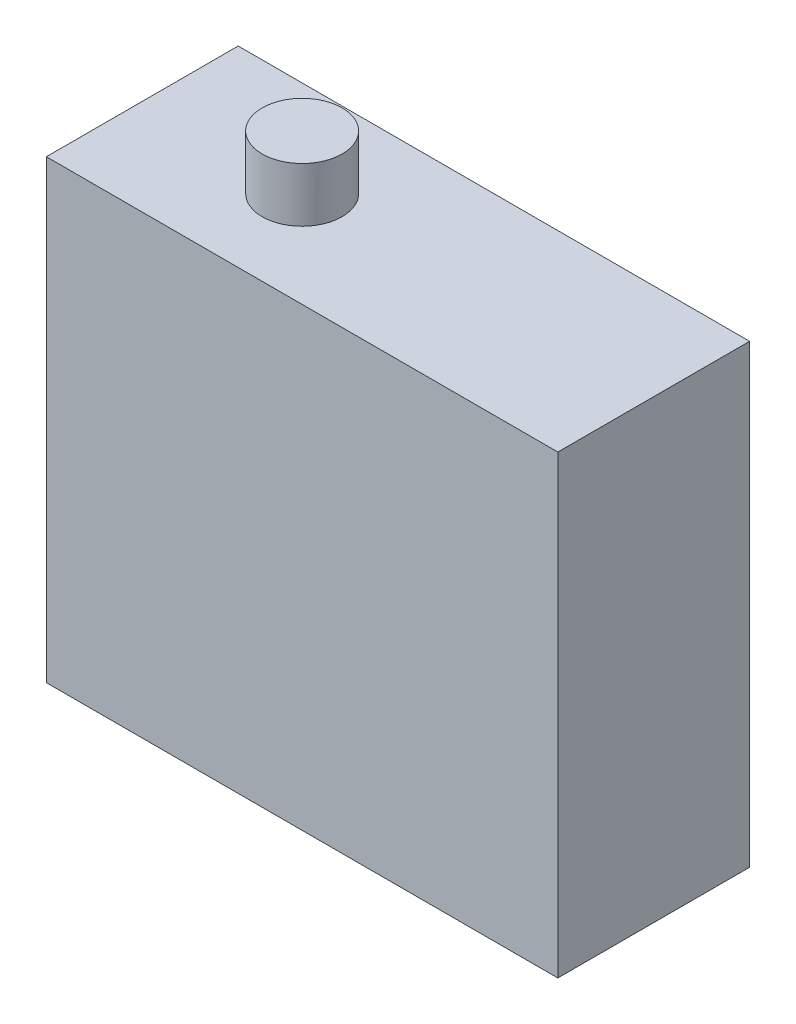
SolidWorks part; units mm, degrees
ref_plane "前视基准面" through (0, 0, 0) normal (0, 0, 1) x (1, 0, 0)
ref_plane "上视基准面" through (0, 0, 0) normal (0, 1, 0) x (1, 0, 0)
ref_plane "右视基准面" through (0, 0, 0) normal (1, 0, 0) x (0, 0, -1)
sketch "草图1" plane through (0, 0, 0) normal (0, 0, 1) x (1, 0, 0)
  line L1 (0, 0) -> (32, 0)
  line L2 (0, 0) -> (0, 28.5)
  line L3 (0, 28.5) -> (32, 28.5)
  line L4 (32, 0) -> (32, 28.5)
  dimension "D1" = 32
  dimension "D2" = 28.5
extrude "凸台-拉伸1" add sketch "草图1" along normal blind 12
sketch "草图2" plane through (0, 28.5, 0) normal (0, 1, 0) x (1, 0, 0)
  line L0 (0, 0) -> (10.0032, 0)
  line L1 (32, 0) -> (0, 0) construction
  line L2 (10.0032, 0) -> (10.0032, -6)
  circle A0 centre (10.0032, -6) radius 2.5
  dimension "D1" = 6
extrude "凸台-拉伸2" add sketch "草图2" along normal blind 3.4 contours A0
